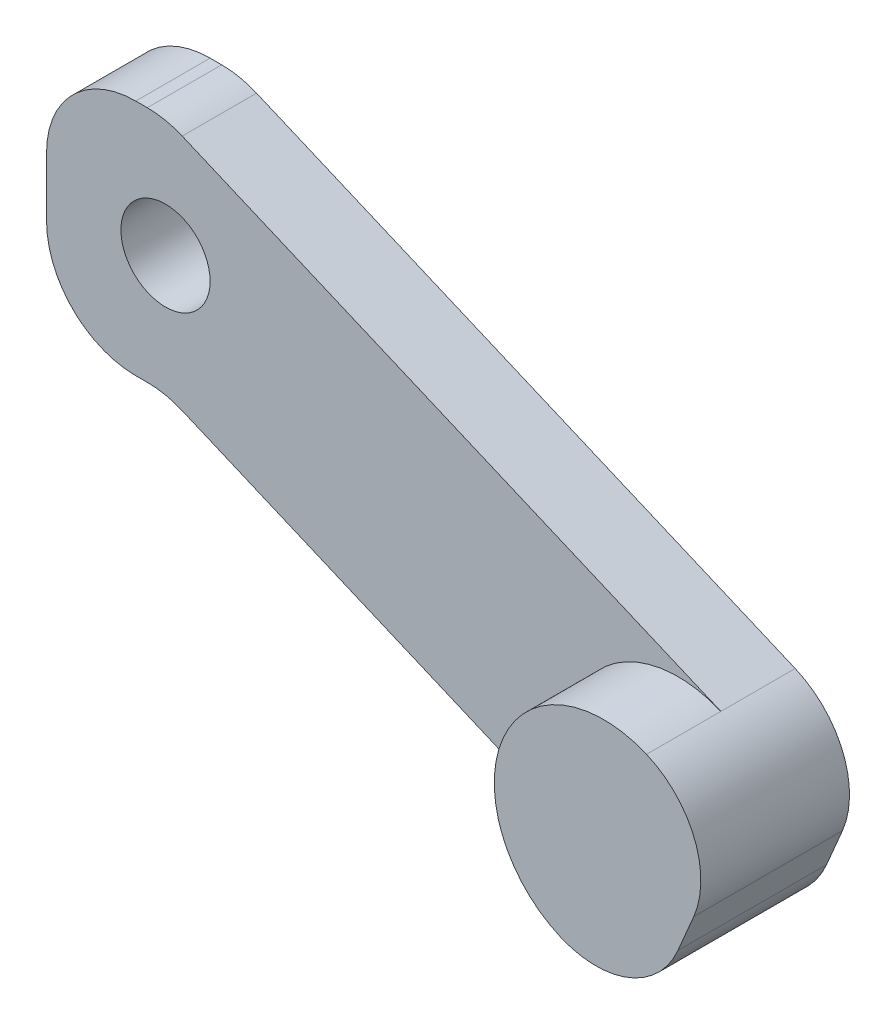
SolidWorks part; units mm, degrees
ref_plane "Plano frontal" through (0, 0, 0) normal (0, 0, 1) x (1, 0, 0)
ref_plane "Plano superior" through (0, 0, 0) normal (0, 1, 0) x (1, 0, 0)
ref_plane "Plano direito" through (0, 0, 0) normal (1, 0, 0) x (0, 0, -1)
sketch "Esboço1" plane through (0, 0, 0) normal (0, 0, 1) x (1, 0, 0)
  line L0 (-8, -8) -> (-8, 8)
  line L5 (-8, 8) -> (0, 8)
  line L6 (0, 8) -> (42.8798, -10.2239)
  line L7 (42.8798, -10.2239) -> (37.1202, -23.7761)
  line L8 (37.1202, -23.7761) -> (0, -8)
  line L9 (0, -8) -> (-8, -8)
  line L10 (-17.8615, 0) -> (30.3176, 0) construction
  circle A0 centre (0, 0) radius 3
  point P0 (0, 0)
  point P14 (40, -17)
  dimension "D3" = 6
  dimension "D1" = 8
  dimension "D2" = 8
  dimension "D4" = 17
  dimension "D5" = 40
extrude "Ressalto-extrusão1" add sketch "Esboço1" along normal blind 5 contours L5 L6 L7 L8 L9 L0 | A0
fillet "Filete1" radius 6 6 edges at (0, -8, 2.5) (-8, -8, 2.5) (-8, 8, 2.5) (0, 8, 2.5) (42.8798, -10.2239, 2.5) (37.1202, -23.7761, 2.5)
sketch "Esboço2" plane through (0, 0, 5) normal (0, 0, 1) x (1, 0, 0)
  line L3 (39.467, -18.2541) -> (40.533, -15.7459)
  line L4 (39.467, -18.2541) -> (40.533, -15.7459)
  arc A4 (37.3578, -7.8771) -> (35.7183, -7.3957) centre (34.478, -14.6532) ccw
  arc A5 (35.7183, -7.3957) -> (31.5982, -21.4292) centre (34.478, -14.6532) ccw
  arc A6 (31.5982, -21.4292) -> (39.467, -18.2541) centre (33.945, -15.9072) ccw
  arc A7 (40.533, -15.7459) -> (37.3578, -7.8771) centre (35.011, -13.3991) ccw
  arc A8 (31.5982, -21.4292) -> (39.467, -18.2541) centre (33.945, -15.9072) ccw
  arc A9 (40.533, -15.7459) -> (37.3578, -7.8771) centre (35.011, -13.3991) ccw
  point P5 (34.6544, -12.817)
  point P9 (0, 0)
  dimension "D1" = 0
extrude "Ressalto-extrusão2" add sketch "Esboço2" along normal blind 5
